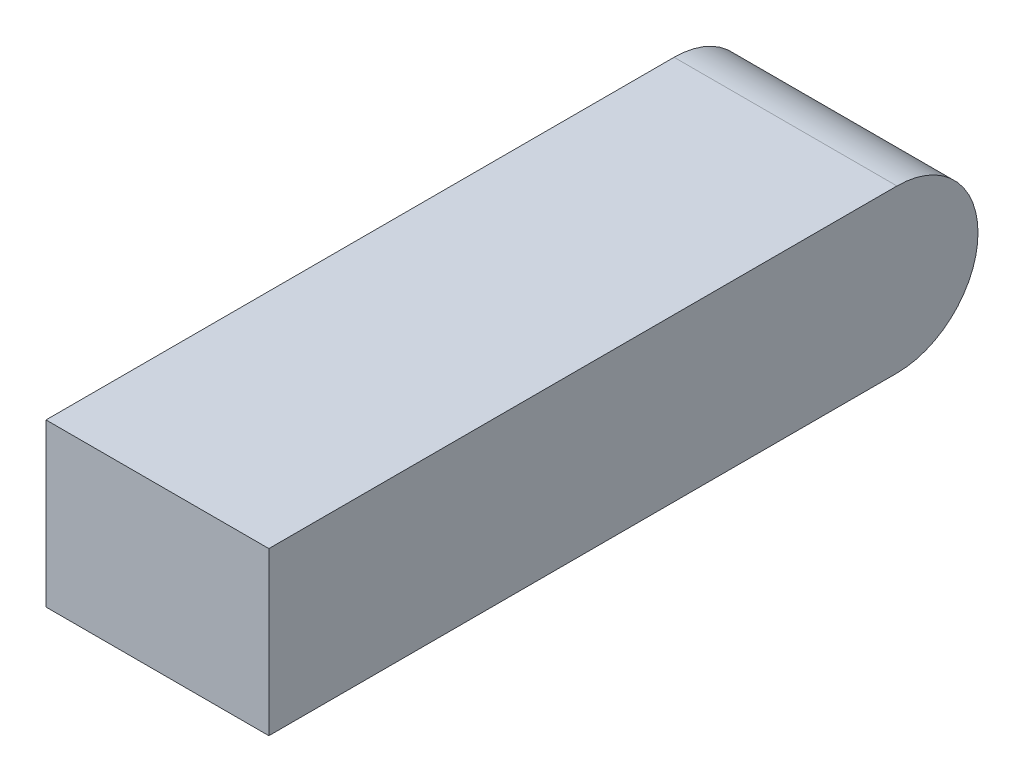
SolidWorks part; units mm, degrees
ref_plane "Front Plane" through (0, 0, 0) normal (0, 0, 1) x (1, 0, 0)
ref_plane "Top Plane" through (0, 0, 0) normal (0, 1, 0) x (1, 0, 0)
ref_plane "Right Plane" through (0, 0, 0) normal (1, 0, 0) x (0, 0, -1)
sketch "Sketch1" plane through (0, 0, 0) normal (1, 0, 0) x (0, 0, -1)
  line L1 (-70, -16) -> (54, -16)
  line L2 (-70, -16) -> (-70, 16)
  line L3 (-70, 16) -> (54, 16)
  line L5 (-70, -16) -> (61.5997, 14.0799) construction
  line L6 (-70, 16) -> (61.5997, -14.0799) construction
  arc A0 (54, -16) -> (54, 16) centre (54, 0) ccw
  point P0 (0, 0)
  point P1 (70, 0)
  point P7 (0, 0)
  point P9 (-4.2001, -0.96)
  dimension "D1" = 140
  dimension "D2" = 32
extrude "Boss-Extrude1" add sketch "Sketch1" along normal mid plane 44
